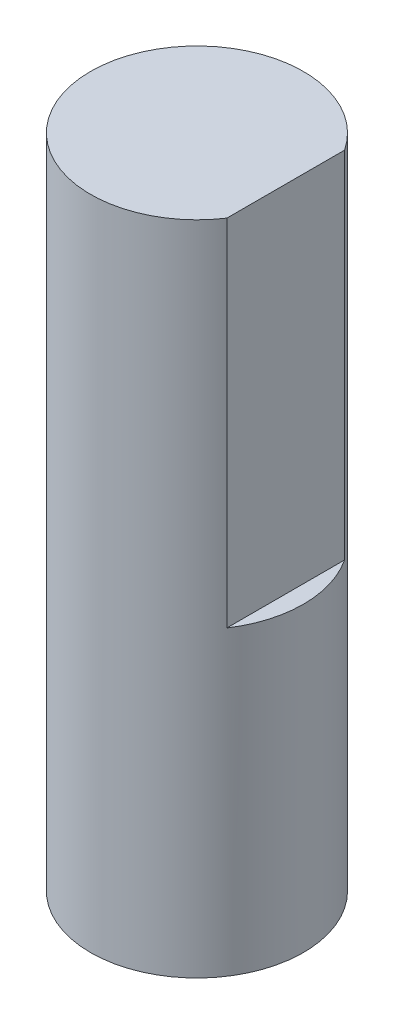
SolidWorks part; units mm, degrees
ref_plane "Front Plane" through (0, 0, 0) normal (0, 0, 1) x (1, 0, 0)
ref_plane "Top Plane" through (0, 0, 0) normal (0, 1, 0) x (1, 0, 0)
ref_plane "Right Plane" through (0, 0, 0) normal (1, 0, 0) x (0, 0, -1)
sketch "Sketch2" plane through (0, 0, 0) normal (0, 1, 0) x (1, 0, 0)
  circle A0 centre (0, 0) radius 3
  dimension "D1" = 6
extrude "Boss-Extrude1" add sketch "Sketch2" along normal blind 18.5
sketch "Sketch3" plane through (0, 18.5, 0) normal (0, 1, 0) x (1, 0, 0)
  line L0 (0, 3.8177) -> (0, -5.5124) construction
  line L1 (-5.2847, 0) -> (6.8154, 0) construction
  line L2 (2.5, 1.6583) -> (2.5, -1.6583)
  circle A0 centre (0, 0) radius 3 construction
  circle A4 centre (0, 0) radius 3
  arc A5 (2.5, -1.6583) -> (2.5, 1.6583) centre (0, 0) ccw
  dimension "D1" = 0
  dimension "D2" = 2.5
extrude "Cut-Extrude1" cut sketch "Sketch3" against normal blind 10
